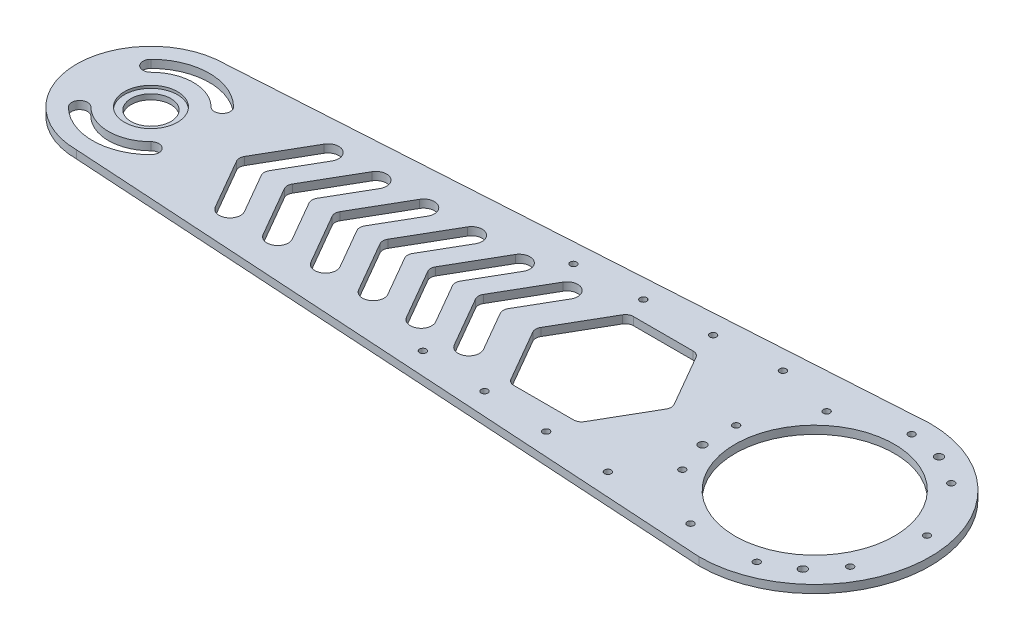
SolidWorks part; units mm, degrees
material "6061 合金"
ref_plane "前视基准面" through (0, 0, 0) normal (0, 0, 1) x (1, 0, 0)
ref_plane "上视基准面" through (0, 0, 0) normal (0, 1, 0) x (1, 0, 0)
ref_plane "右视基准面" through (0, 0, 0) normal (1, 0, 0) x (0, 0, -1)
other "Configuration Table"
sketch "草图1" plane through (0, 0, 0) normal (0, 1, 0) x (1, 0, 0)
  line L0 (0, -43.5) -> (0, 43.5) construction
  line L1 (0, 0) -> (-27.9613, 33.3229) construction
  line L2 (0, 0) -> (27.9613, 33.3229) construction
  line L3 (0, 0) -> (14.8779, 40.8766) construction
  line L4 (0, 0) -> (-250, 0) construction
  line L5 (-230.201, -19.799) -> (-269.799, 19.799) construction
  line L6 (-269.799, -19.799) -> (-230.201, 19.799) construction
  line L7 (0, 28) -> (-250, 28) construction
  line L8 (0, 28) -> (0, -28) construction
  line L9 (0, -28) -> (-250, -28) construction
  line L10 (-250, 28) -> (-250, -28) construction
  line L11 (-125, -28) -> (-125, 28) construction
  line L12 (0, 0) -> (-250, 0) construction
  line L13 (-250, 0) -> (-250, 18.6396) construction
  line L14 (-250, 0) -> (-236.565, 13.435) construction
  line L15 (-250, 0) -> (-263.435, 13.435) construction
  line L16 (-250, 28) -> (0, 43.5) construction
  line L17 (-250, -28) -> (0, -43.5) construction
  circle A0 centre (0, 0) radius 43.5 construction
  circle A1 centre (0, 0) radius 36.5 construction
  circle A2 centre (0, 0) radius 30 construction
  circle A7 centre (-23.4617, 27.9606) radius 1.25 construction
  circle A8 centre (0, 36.5) radius 1.25 construction
  circle A9 centre (12.4837, 34.2988) radius 1.5 construction
  circle A10 centre (23.4617, 27.9606) radius 1.25 construction
  circle A11 centre (35.9455, 6.3382) radius 1.25 construction
  circle A12 centre (31.6099, -18.25) radius 1.25 construction
  circle A13 centre (23.4617, -27.9606) radius 1.5 construction
  circle A14 centre (12.4837, -34.2988) radius 1.25 construction
  circle A15 centre (-12.4837, -34.2988) radius 1.25 construction
  circle A16 centre (-31.6099, -18.25) radius 1.25 construction
  circle A17 centre (-35.9455, -6.3382) radius 1.5 construction
  circle A18 centre (-35.9455, 6.3382) radius 1.25 construction
  circle A19 centre (-250, 0) radius 28 construction
  circle A20 centre (-250, 0) radius 22 construction
  circle A21 centre (-250, 0) radius 16 construction
  arc A22 (-263.435, 13.435) -> (-236.565, 13.435) centre (-250, 0) cw construction
  arc A23 (-234.4463, 15.5537) -> (-265.5537, 15.5537) centre (-250, 0) ccw construction
  arc A24 (-238.6836, 11.3164) -> (-261.3164, 11.3164) centre (-250, 0) ccw construction
  arc A25 (-238.6836, 11.3164) -> (-234.4463, 15.5537) centre (-236.565, 13.435) ccw construction
  arc A26 (-265.5537, 15.5537) -> (-261.3164, 11.3164) centre (-263.435, 13.435) ccw construction
  circle A27 centre (-250, 0) radius 4 construction
  circle A28 centre (-250, 4) radius 1.25 construction
  circle A29 centre (-254, 0) radius 1.25 construction
  circle A30 centre (-250, -4) radius 1.25 construction
  circle A31 centre (-246, 0) radius 1.25 construction
  arc A32 (-263.435, -13.435) -> (-236.565, -13.435) centre (-250, 0) ccw construction
  arc A33 (-234.4463, -15.5537) -> (-265.5537, -15.5537) centre (-250, 0) cw construction
  arc A34 (-238.6836, -11.3164) -> (-261.3164, -11.3164) centre (-250, 0) cw construction
  arc A35 (-238.6836, -11.3164) -> (-234.4463, -15.5537) centre (-236.565, -13.435) cw construction
  arc A36 (-265.5537, -15.5537) -> (-261.3164, -11.3164) centre (-263.435, -13.435) cw construction
  point P8 (0, 0)
  point P24 (-125, 0)
  point P42 (0, 0)
  point P44 (-250, 0)
  point P53 (-250, 19)
  point P71 (-250, -19)
  dimension "D1" = 3
ref_plane "基准面1" through (0, 5, 0) normal (0, 1, 0) x (1, 0, 0)
sketch "草图2" plane through (0, 5, 0) normal (0, 1, 0) x (1, 0, 0)
  line L0 (-250, 28) -> (0, 43.5)
  line L1 (-250, -28) -> (0, -43.5)
  arc A0 (-250, 28) -> (-250, -28) centre (-250, 0) ccw
  arc A1 (0, 43.5) -> (0, -43.5) centre (0, 0) cw
extrude "凸台-拉伸1" add sketch "草图2" along normal blind 3
sketch3d "3D草图1"
  point P0 (-145.9567, 8, -3.4646)
ref_plane "基准面2" through (0, 8, 0) normal (0, 1, 0) x (1, 0, 0)
sketch "草图3" plane through (0, 8, 0) normal (0, 1, 0) x (1, 0, 0)
  circle A0 centre (-250, 4) radius 1.25
  circle A1 centre (-246, 0) radius 1.25
  circle A2 centre (-250, -4) radius 1.25
  circle A3 centre (-254, 0) radius 1.25
  circle A4 centre (0, 0) radius 30
  circle A5 centre (0, 36.5) radius 1.25
  circle A6 centre (12.4837, 34.2988) radius 1.5
  circle A7 centre (23.4617, 27.9606) radius 1.25
  circle A8 centre (-23.4617, 27.9606) radius 1.25
  circle A9 centre (-35.9455, 6.3382) radius 1.25
  circle A10 centre (-35.9455, -6.3382) radius 1.5
  circle A11 centre (-31.6099, -18.25) radius 1.25
  circle A12 centre (-12.4837, -34.2988) radius 1.25
  circle A13 centre (12.4837, -34.2988) radius 1.25
  circle A14 centre (23.4617, -27.9606) radius 1.5
  circle A15 centre (31.6099, -18.25) radius 1.25
  circle A16 centre (35.9455, 6.3382) radius 1.25
  arc A17 (-265.5537, 15.5537) -> (-261.3164, 11.3164) centre (-263.435, 13.435) ccw
  arc A18 (-238.6836, 11.3164) -> (-234.4463, 15.5537) centre (-236.565, 13.435) ccw
  arc A19 (-234.4463, 15.5537) -> (-265.5537, 15.5537) centre (-250, 0) ccw
  arc A20 (-261.3164, 11.3164) -> (-238.6836, 11.3164) centre (-250, 0) cw
  arc A21 (-261.3164, -11.3164) -> (-238.6836, -11.3164) centre (-250, 0) ccw
  arc A22 (-234.4463, -15.5537) -> (-265.5537, -15.5537) centre (-250, 0) cw
  arc A23 (-265.5537, -15.5537) -> (-261.3164, -11.3164) centre (-263.435, -13.435) cw
  arc A24 (-238.6836, -11.3164) -> (-234.4463, -15.5537) centre (-236.565, -13.435) cw
extrude "切除-拉伸1" cut sketch "草图3" against normal blind 3
sketch3d "3D草图2"
  point P0 (-118.6358, 8, -10.1958)
ref_plane "基准面3" through (0, 8, 0) normal (0, 1, 0) x (1, 0, 0)
sketch "草图4" plane through (0, 8, 0) normal (0, 1, 0) x (1, 0, 0)
  line L0 (0, 0) -> (-250, 0) construction
  line L1 (-222.1049, 0) -> (-217.1049, 0) construction
  line L3 (-217.1049, 0) -> (-210.1249, -4.0299) construction
  line L4 (-217.1049, 0) -> (-205.2675, 20.5031) construction
  line L5 (-205.2675, 20.5031) -> (-198.2874, 16.4731) construction
  line L6 (-210.1249, -4.0299) -> (-198.2874, 16.4731) construction
  line L7 (-217.1049, 0) -> (-198.2874, 16.4731) construction
  line L8 (-205.2675, 20.5031) -> (-210.1249, -4.0299) construction
  line L28 (-214.6027, 0) -> (-194.6027, 0) construction
  line L29 (-115.7976, 0) -> (-43.3199, 0) construction
  line L30 (-216.2389, 1.5) -> (-205.2675, 20.5031)
  line L31 (-54.444, 1.5) -> (-65.7024, 21)
  line L32 (-68.3004, 22.5) -> (-90.8171, 22.5)
  line L33 (-93.4152, 21) -> (-104.6735, 1.5)
  line L34 (-104.6735, -1.5) -> (-93.4152, -21)
  line L35 (-90.8171, -22.5) -> (-68.3004, -22.5)
  line L36 (-65.7024, -21) -> (-54.444, -1.5)
  line L37 (-206.9322, 1.5) -> (-198.2874, 16.4731)
  line L38 (-206.9322, -1.5) -> (-198.2874, -16.4731)
  line L39 (-216.2389, -1.5) -> (-205.2675, -20.5031)
  line L40 (-188.9322, -1.5) -> (-180.2874, -16.4731)
  line L41 (-198.2389, -1.5) -> (-187.2675, -20.5031)
  line L42 (-198.2389, 1.5) -> (-187.2675, 20.5031)
  line L43 (-188.9322, 1.5) -> (-180.2874, 16.4731)
  line L44 (-170.9322, -1.5) -> (-162.2874, -16.4731)
  line L45 (-180.2389, -1.5) -> (-169.2675, -20.5031)
  line L46 (-180.2389, 1.5) -> (-169.2675, 20.5031)
  line L47 (-170.9322, 1.5) -> (-162.2874, 16.4731)
  line L48 (-152.9322, -1.5) -> (-144.2874, -16.4731)
  line L49 (-162.2389, -1.5) -> (-151.2675, -20.5031)
  line L50 (-162.2389, 1.5) -> (-151.2675, 20.5031)
  line L51 (-152.9322, 1.5) -> (-144.2874, 16.4731)
  line L52 (-134.9322, -1.5) -> (-126.2874, -16.4731)
  line L53 (-144.2389, -1.5) -> (-133.2675, -20.5031)
  line L54 (-144.2389, 1.5) -> (-133.2675, 20.5031)
  line L55 (-134.9322, 1.5) -> (-126.2874, 16.4731)
  line L56 (-116.9322, -1.5) -> (-108.2874, -16.4731)
  line L57 (-126.2389, -1.5) -> (-115.2675, -20.5031)
  line L58 (-126.2389, 1.5) -> (-115.2675, 20.5031)
  line L59 (-116.9322, 1.5) -> (-108.2874, 16.4731)
  line L60 (-206.9322, -1.5) -> (-188.9322, -1.5) construction
  arc A0 (-205.2675, 20.5031) -> (-198.2874, 16.4731) centre (-201.7775, 18.4881) cw construction
  circle A21 centre (-79.5588, 0) radius 22.5 construction
  arc A22 (-93.4152, 21) -> (-90.8171, 22.5) centre (-90.8171, 19.5) cw
  arc A23 (-104.6735, -1.5) -> (-104.6735, 1.5) centre (-102.0754, 0) cw
  arc A24 (-90.8171, -22.5) -> (-93.4152, -21) centre (-90.8171, -19.5) cw
  arc A25 (-65.7024, -21) -> (-68.3004, -22.5) centre (-68.3004, -19.5) cw
  arc A26 (-54.444, 1.5) -> (-54.444, -1.5) centre (-57.0421, 0) cw
  arc A27 (-65.7024, 21) -> (-68.3004, 22.5) centre (-68.3004, 19.5) ccw
  arc A28 (-205.2675, 20.5031) -> (-198.2874, 16.4731) centre (-201.7775, 18.4881) cw
  arc A29 (-205.2675, -20.5031) -> (-198.2874, -16.4731) centre (-201.7775, -18.4881) ccw
  arc A30 (-216.2389, -1.5) -> (-216.2389, 1.5) centre (-213.6408, 0) cw
  arc A31 (-206.9322, -1.5) -> (-206.9322, 1.5) centre (-204.3341, 0) cw
  arc A32 (-188.9322, -1.5) -> (-188.9322, 1.5) centre (-186.3341, 0) cw
  arc A33 (-187.2675, -20.5031) -> (-180.2874, -16.4731) centre (-183.7775, -18.4881) ccw
  arc A34 (-198.2389, -1.5) -> (-198.2389, 1.5) centre (-195.6408, 0) cw
  arc A35 (-187.2675, 20.5031) -> (-180.2874, 16.4731) centre (-183.7775, 18.4881) cw
  arc A36 (-170.9322, -1.5) -> (-170.9322, 1.5) centre (-168.3341, 0) cw
  arc A37 (-169.2675, -20.5031) -> (-162.2874, -16.4731) centre (-165.7775, -18.4881) ccw
  arc A38 (-180.2389, -1.5) -> (-180.2389, 1.5) centre (-177.6408, 0) cw
  arc A39 (-169.2675, 20.5031) -> (-162.2874, 16.4731) centre (-165.7775, 18.4881) cw
  arc A40 (-152.9322, -1.5) -> (-152.9322, 1.5) centre (-150.3341, 0) cw
  arc A41 (-151.2675, -20.5031) -> (-144.2874, -16.4731) centre (-147.7775, -18.4881) ccw
  arc A42 (-162.2389, -1.5) -> (-162.2389, 1.5) centre (-159.6408, 0) cw
  arc A43 (-151.2675, 20.5031) -> (-144.2874, 16.4731) centre (-147.7775, 18.4881) cw
  arc A44 (-134.9322, -1.5) -> (-134.9322, 1.5) centre (-132.3341, 0) cw
  arc A45 (-133.2675, -20.5031) -> (-126.2874, -16.4731) centre (-129.7775, -18.4881) ccw
  arc A46 (-144.2389, -1.5) -> (-144.2389, 1.5) centre (-141.6408, 0) cw
  arc A47 (-133.2675, 20.5031) -> (-126.2874, 16.4731) centre (-129.7775, 18.4881) cw
  arc A48 (-116.9322, -1.5) -> (-116.9322, 1.5) centre (-114.3341, 0) cw
  arc A49 (-115.2675, -20.5031) -> (-108.2874, -16.4731) centre (-111.7775, -18.4881) ccw
  arc A50 (-126.2389, -1.5) -> (-126.2389, 1.5) centre (-123.6408, 0) cw
  arc A51 (-115.2675, 20.5031) -> (-108.2874, 16.4731) centre (-111.7775, 18.4881) cw
  point P19 (-207.7982, 0)
  point P23 (-207.7982, 0)
  dimension "D2" = 3
  dimension "D5" = 3
  dimension "D6" = 3
  dimension "D7" = 3
  dimension "D8" = 3
  dimension "D9" = 3
  dimension "D10" = 3
  dimension "D11" = 18
  dimension "D3" = 3
  dimension "D4" = 6
extrude "切除-拉伸2" cut sketch "草图4" against normal blind 3
ref_plane "基准面4" through (0, 8, 0) normal (0, 1, 0) x (1, 0, 0)
sketch "草图5" plane through (0, 8, 0) normal (0, 1, 0) x (1, 0, 0)
  line L0 (-125, 0) -> (-43.5, 0) construction
  line L5 (-125, 28) -> (-27.1878, 34.0644) construction
  line L6 (0, 0) -> (-250, 0) construction
  line L11 (-250, 28) -> (0, 43.5) construction
  circle A3 centre (-44.9417, 32.9636) radius 1.25
  circle A4 centre (-69.7029, 31.4284) radius 1.25
  circle A7 centre (-119.2253, 28.358) radius 1.25
  circle A8 centre (-94.4641, 29.8932) radius 1.25
  circle A9 centre (0, 0) radius 43.5 construction
  circle A10 centre (-44.9417, -32.9636) radius 1.25
  circle A11 centre (-69.7029, -31.4284) radius 1.25
  circle A12 centre (-94.4641, -29.8932) radius 1.25
  circle A13 centre (-119.2253, -28.358) radius 1.25
  point P3 (-62.5299, 31.5812)
  point P4 (-62.5299, 31.5812)
extrude "切除-拉伸3" cut sketch "草图5" against normal blind 10
sketch3d "3D草图3"
  point P0 (-248.0252, 8, -6.8442)
ref_plane "基准面5" through (0, 8, 0) normal (0, 1, 0) x (1, 0, 0)
sketch "草图6" plane through (0, 8, 0) normal (0, 1, 0) x (1, 0, 0)
  line L0 (-230.201, -19.799) -> (-269.799, 19.799) construction
  circle A0 centre (-250, 0) radius 10
extrude "切除-拉伸4" cut sketch "草图6" against normal blind 1
sketch3d "3D草图4"
  point P0 (-254.5557, 7, -3.036)
ref_plane "基准面6" through (0, 7, 0) normal (0, 1, 0) x (1, 0, 0)
sketch "草图7" plane through (0, 7, 0) normal (0, 1, 0) x (1, 0, 0)
  circle A0 centre (-250, 0) radius 7.5
extrude "切除-拉伸5" cut sketch "草图7" against normal blind 11
